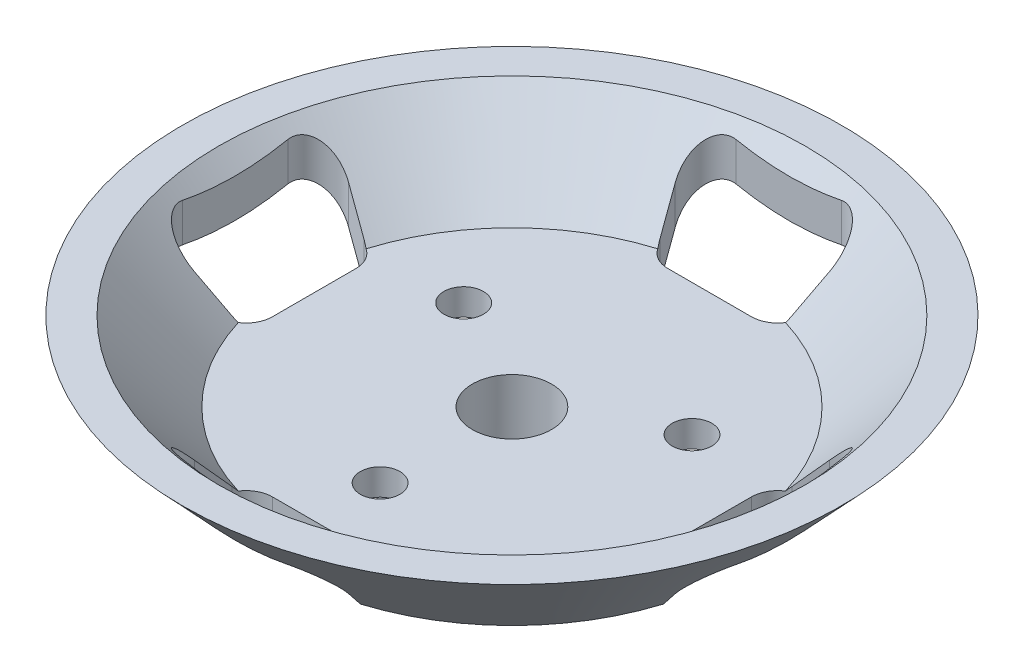
SolidWorks part; units mm, degrees
ref_plane "Front Plane" through (0, 0, 0) normal (0, 0, 1) x (1, 0, 0)
ref_plane "Top Plane" through (0, 0, 0) normal (0, 1, 0) x (1, 0, 0)
ref_plane "Right Plane" through (0, 0, 0) normal (1, 0, 0) x (0, 0, -1)
sketch "Sketch1" plane through (0, 0, 0) normal (0, 1, 0) x (1, 0, 0)
  circle A0 centre (0, 0) radius 17.5
  dimension "D1" = 35
ref_plane "Plane1" through (0, 8, 0) normal (0, 1, 0) x (1, 0, 0)
sketch "Sketch2" plane through (0, 8, 0) normal (0, 1, 0) x (1, 0, 0)
  circle A0 centre (0, 0) radius 25
  dimension "D1" = 50
loft "Loft1" add profiles "Sketch1", "Sketch2"
shell "Shell1" thickness 2
sketch "Sketch3" plane through (0, 0, 0) normal (0, -1, 0) x (1, 0, 0)
  circle A0 centre (0, 0) radius 7.25
  circle A1 centre (0, 0) radius 3
  dimension "D1" = 14.5
  dimension "D2" = 6
extrude "Boss-Extrude1" add sketch "Sketch3" along normal blind 5
sketch "Sketch4" plane through (0, 0, 0) normal (0, -1, 0) x (1, 0, 0)
  circle A1 centre (0, 0) radius 3
  circle A2 centre (0, 0) radius 3
  dimension "D1" = 0
extrude "Cut-Extrude1" cut sketch "Sketch4" against normal blind 5
sketch "Sketch5" plane through (0, 0, 0) normal (0, -1, 0) x (1, 0, 0)
  circle A0 centre (0, 0) radius 10 construction
  circle A1 centre (0, 10) radius 1.5
  circle A2 centre (8.6603, -5) radius 1.5
  circle A3 centre (-8.6603, -5) radius 1.5
  point P11 (0, 0)
  dimension "D1" = 20
  dimension "D2" = 3
  dimension "D4" = 17.3205
  dimension "D5" = 8.6603
  dimension "D3" = 3
extrude "Cut-Extrude2" cut sketch "Sketch5" against normal through all
sketch "Sketch6" plane through (0, -5, 0) normal (0, -1, 0) x (1, 0, 0)
  line L0 (-5.0128, 16.2308) -> (-5.8462, 18.2308)
  line L1 (-4, 21) -> (4, 21)
  line L2 (5.8462, 18.2308) -> (5.0128, 16.2308)
  line L3 (3.1667, 15) -> (-3.1667, 15)
  line L4 (15, -3.1667) -> (15, 3.1667)
  line L5 (16.2308, 5.0128) -> (18.2308, 5.8462)
  line L6 (21, 4) -> (21, -4)
  line L7 (18.2308, -5.8462) -> (16.2308, -5.0128)
  line L8 (-3.1667, -15) -> (3.1667, -15)
  line L9 (5.0128, -16.2308) -> (5.8462, -18.2308)
  line L10 (4, -21) -> (-4, -21)
  line L11 (-5.8462, -18.2308) -> (-5.0128, -16.2308)
  line L12 (-15, 3.1667) -> (-15, -3.1667)
  line L13 (-16.2308, -5.0128) -> (-18.2308, -5.8462)
  line L14 (-21, -4) -> (-21, 4)
  line L15 (-18.2308, 5.8462) -> (-16.2308, 5.0128)
  arc A0 (-3.1667, 15) -> (-5.0128, 16.2308) centre (-3.1667, 17) cw
  arc A1 (5.0128, 16.2308) -> (3.1667, 15) centre (3.1667, 17) cw
  arc A2 (5.8462, 18.2308) -> (4, 21) centre (4, 19) ccw
  arc A3 (-5.8462, 18.2308) -> (-4, 21) centre (-4, 19) cw
  arc A4 (16.2308, -5.0128) -> (15, -3.1667) centre (17, -3.1667) cw
  arc A5 (15, 3.1667) -> (16.2308, 5.0128) centre (17, 3.1667) cw
  arc A6 (18.2308, 5.8462) -> (21, 4) centre (19, 4) cw
  arc A7 (18.2308, -5.8462) -> (21, -4) centre (19, -4) ccw
  arc A8 (-5.0128, -16.2308) -> (-3.1667, -15) centre (-3.1667, -17) cw
  arc A9 (3.1667, -15) -> (5.0128, -16.2308) centre (3.1667, -17) cw
  arc A10 (5.8462, -18.2308) -> (4, -21) centre (4, -19) cw
  arc A11 (-5.8462, -18.2308) -> (-4, -21) centre (-4, -19) ccw
  arc A12 (-16.2308, 5.0128) -> (-15, 3.1667) centre (-17, 3.1667) cw
  arc A13 (-15, -3.1667) -> (-16.2308, -5.0128) centre (-17, -3.1667) cw
  arc A14 (-18.2308, -5.8462) -> (-21, -4) centre (-19, -4) cw
  arc A15 (-18.2308, 5.8462) -> (-21, 4) centre (-19, 4) ccw
  point P4 (0, 15)
  point P5 (0, 21)
  point P9 (-4.5, 15)
  point P12 (4.5, 15)
  point P17 (-7, 21)
  point P18 (0, 0)
  point P20 (0, 0)
  point P57 (0, 0)
  dimension "D5" = 2
  dimension "D1" = 15
  dimension "D2" = 9
  dimension "D3" = 6
  dimension "D4" = 7
  dimension "D7" = 15
  dimension "D8" = 3.1667
  dimension "D6" = 4
extrude "Cut-Extrude3" cut sketch "Sketch6" against normal blind 15
